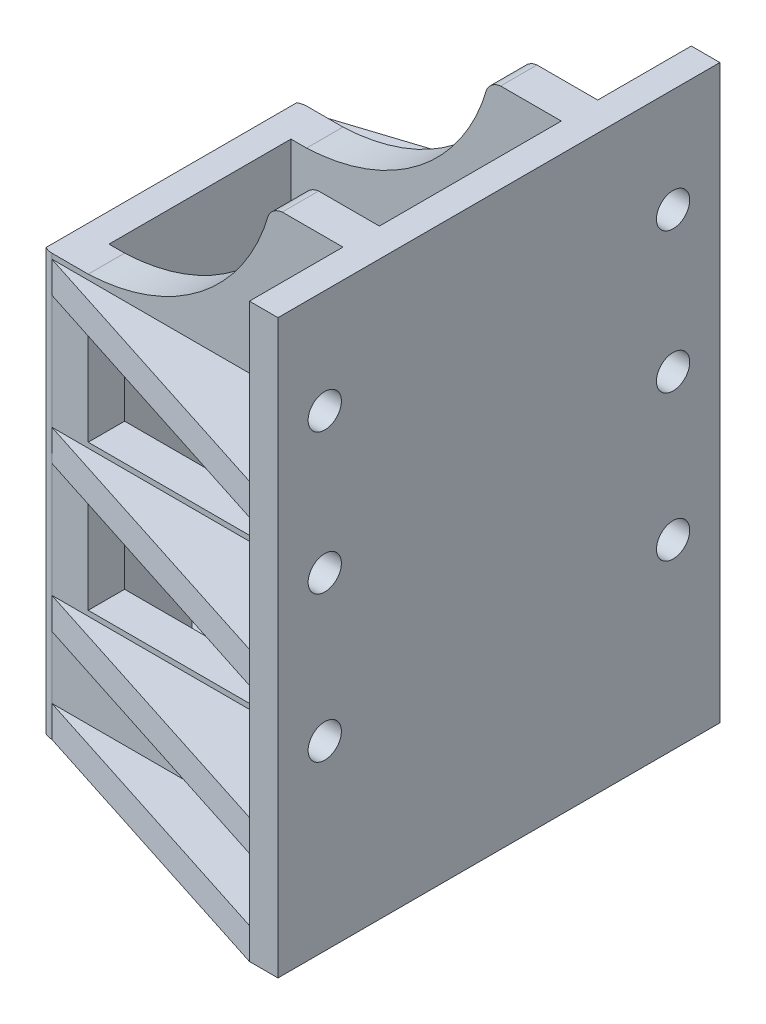
SolidWorks part; units mm, degrees
ref_plane "Plano frontal" through (0, 0, 0) normal (0, 0, 1) x (1, 0, 0)
ref_plane "Plano superior" through (0, 0, 0) normal (0, 1, 0) x (1, 0, 0)
ref_plane "Plano direito" through (0, 0, 0) normal (1, 0, 0) x (0, 0, -1)
sketch "Esboço1" plane through (0, 0, 0) normal (0, 1, 0) x (1, 0, 0)
  line L10 (15, 12.25) -> (16.5, 12.25)
  line L11 (-15, 12.25) -> (15, 12.25)
  line L12 (-16.5, 10.75) -> (-16.5, -10.75)
  line L13 (-15, -12.25) -> (15, -12.25)
  line L14 (16.5, 10.75) -> (16.5, -10.75)
  line L15 (16.5, 10.75) -> (16.5, 12.25)
  line L16 (15, -12.25) -> (16.5, -12.25)
  line L17 (16.5, -10.75) -> (16.5, -12.25)
  arc A2 (-16.5, -10.75) -> (-15, -12.25) centre (-15, -10.75) ccw
  arc A3 (-16.5, 10.75) -> (-15, 12.25) centre (-15, 10.75) cw
extrude "Ressalto-extrusão1" add sketch "Esboço1" along normal blind 55
sketch "Esboço2" plane through (0, 55, 0) normal (0, 1, 0) x (1, 0, 0)
  line L0 (-13, 8.75) -> (-13, -8.75)
  line L1 (13, 8.75) -> (13, -8.75)
  line L2 (-13, -8.75) -> (13, -8.75)
  line L3 (-13, 8.75) -> (13, 8.75)
extrude "Corte-extrusão1" cut sketch "Esboço2" against normal blind 52
sketch "Esboço3" plane through (-16.5, 0, 0) normal (-1, 0, 0) x (0, 0, 1)
  line L0 (-4.25, 8) -> (0.75, 8)
  line L1 (0.75, 8) -> (0.75, 3)
  line L2 (-4.25, 3) -> (0.75, 3)
  line L3 (-12.25, 3) -> (-12.25, 8)
  line L5 (-12.25, 3) -> (-4.25, 3)
  line L7 (-4.25, 8) -> (-12.25, 8)
extrude "Corte-extrusão2" cut sketch "Esboço3" against normal blind 29.5
sketch "Esboço4" plane through (0, 0, -12.25) normal (0, 0, -1) x (-1, 0, 0)
  line L0 (-11.5, 22.5) -> (-11.5, 12.5)
  line L1 (11.5, 36.5) -> (11.5, 26.5)
  line L2 (11.5, 40.5) -> (24.9424, 40.5)
  line L3 (11.5, 22.5) -> (11.5, 12.5)
  line L4 (-11.5, 36.5) -> (-11.5, 26.5)
  line L5 (24.9424, 40.5) -> (24.9424, 59.8345)
  line L6 (24.9424, 59.8345) -> (-1.5, 59.8345)
  line L7 (-16.5, 55) -> (-16.5, 57.6308)
  line L12 (-16.5, 57.6308) -> (-7.5761, 57.6308)
  line L15 (-11.5, 36.5) -> (11.5, 36.5)
  line L16 (-11.5, 26.5) -> (11.5, 26.5)
  line L17 (-11.5, 22.5) -> (11.5, 22.5)
  line L18 (-11.5, 12.5) -> (11.5, 12.5)
  line L21 (-6.0761, 62.0924) -> (-1.5, 59.8345)
  line L22 (-16.5, 55) -> (-7.5761, 55)
  line L23 (-6.0761, 62.0924) -> (-7.5761, 62.0924)
  line L24 (-7.5761, 62.0924) -> (-7.5761, 57.6308)
  line L25 (-7.5761, 55) -> (-7.1577, 55)
  arc A1 (-7.1577, 55) -> (-5.834, 54.0753) centre (-7.3669, 53.2908) cw
  arc A2 (-5.834, 54.0753) -> (11.5, 40.5) centre (12.2414, 59.301) ccw
extrude "Corte-extrusão3" cut sketch "Esboço4" against normal blind 52
sketch "Esboço5" plane through (0, 0, 0) normal (0, -1, 0) x (1, 0, 0)
  line L9 (-10, 8) -> (10, 8)
  line L10 (-10, 8) -> (-10, -8)
  line L11 (-10, -8) -> (10, -8)
  line L12 (10, 8) -> (10, -8)
extrude "Corte-extrusão4" cut sketch "Esboço5" against normal blind 52
sketch "Esboço6" plane through (0, 0, -12.25) normal (0, 0, -1) x (-1, 0, 0)
  line L2 (-16.5, 55) -> (-13, 55)
  line L12 (-8.2604, 40) -> (15, 40)
  line L13 (-8.2604, 37) -> (15, 37)
  line L14 (15, 26) -> (15, 23)
  line L15 (-8.2604, 40) -> (-13, 40)
  line L16 (15, 12) -> (15, 9)
  line L17 (-8.2604, 37) -> (-13, 37)
  line L18 (-8.2604, 26) -> (15, 26)
  line L19 (-8.2604, 26) -> (-13, 26)
  line L20 (-8.2604, 23) -> (-13, 23)
  line L21 (15, 3) -> (15, 0)
  line L22 (-8.2604, 23) -> (15, 23)
  line L23 (-16.5, 55) -> (-16.5, 0)
  line L24 (-8.2604, 12) -> (15, 12)
  line L25 (-8.2604, 12) -> (-13, 12)
  line L27 (-16.5, 0) -> (15, 0)
  line L28 (-13, 40) -> (-13, 55)
  line L29 (-8.2604, 9) -> (15, 9)
  line L30 (-8.2604, 9) -> (-13, 9)
  line L32 (-13, 3) -> (15, 3)
  line L33 (-13, 9) -> (-13, 3)
  line L34 (15, 40) -> (15, 37)
  line L35 (-13, 37) -> (-13, 26)
  line L37 (-13, 23) -> (-13, 12)
extrude "Ressalto-extrusão3" add sketch "Esboço6" along normal blind 9
sketch "Esboço9" plane through (0, 0, 12.25) normal (0, 0, 1) x (1, 0, 0)
  line L25 (13, 23) -> (13, 12)
  line L26 (13, 37) -> (13, 26)
  line L27 (-15, 40) -> (-15, 37)
  line L28 (13, 9) -> (13, 3)
  line L29 (13, 3) -> (-15, 3)
  line L30 (8.2604, 9) -> (13, 9)
  line L31 (8.2604, 9) -> (-15, 9)
  line L32 (13, 40) -> (13, 55)
  line L33 (16.5, 0) -> (-15, 0)
  line L34 (8.2604, 12) -> (13, 12)
  line L35 (8.2604, 12) -> (-15, 12)
  line L36 (16.5, 55) -> (16.5, 0)
  line L37 (8.2604, 23) -> (-15, 23)
  line L38 (-15, 3) -> (-15, 0)
  line L39 (8.2604, 23) -> (13, 23)
  line L40 (8.2604, 26) -> (13, 26)
  line L41 (8.2604, 26) -> (-15, 26)
  line L42 (8.2604, 37) -> (13, 37)
  line L43 (-15, 12) -> (-15, 9)
  line L44 (8.2604, 40) -> (13, 40)
  line L45 (-15, 26) -> (-15, 23)
  line L46 (8.2604, 37) -> (-15, 37)
  line L47 (8.2604, 40) -> (-15, 40)
  line L48 (16.5, 55) -> (13, 55)
extrude "Ressalto-extrusão4" add sketch "Esboço9" along normal blind 9
sketch "Esboço11" plane through (0, 55, 0) normal (0, 1, 0) x (1, 0, 0)
  line L0 (13, 21.25) -> (-15, 12.25)
  line L1 (-15, 12.25) -> (-18.3963, 13.557)
  line L2 (-18.3963, 13.557) -> (-20.171, 2.9688)
  line L3 (-20.171, 2.9688) -> (-21.6877, -13.9298)
  line L4 (-21.6877, -13.9298) -> (-19.2836, -16.808)
  line L5 (-19.2836, -16.808) -> (-15, -12.25)
  line L6 (-15, -12.25) -> (13, -21.25)
  line L7 (13, -21.25) -> (12.3873, -22.8422)
  line L8 (12.3873, -22.8422) -> (-13.7336, -25.767)
  line L9 (-13.7336, -25.767) -> (-25.5939, -17.7036)
  line L10 (-25.5939, -17.7036) -> (-24.1015, -8.7999)
  line L11 (-24.1015, -8.7999) -> (-21.4044, 21.25)
  line L12 (-21.4044, 21.25) -> (-11.3429, 26.8191)
  line L13 (-11.3429, 26.8191) -> (13.3468, 26.8191)
  line L14 (13.3468, 26.8191) -> (13, 21.25)
extrude "Corte-extrusão7" cut sketch "Esboço11" against normal through all
sketch "Esboço12" plane through (13, 0, 0) normal (-1, 0, 0) x (0, 0, 1)
  circle A0 centre (-16.75, 45) radius 1.6
  circle A1 centre (-16.75, 31.5) radius 1.6
  circle A2 centre (-16.75, 17.5) radius 1.6
  circle A3 centre (16.75, 17.5) radius 1.6
  circle A4 centre (16.75, 31.5) radius 1.6
  circle A5 centre (16.75, 45) radius 1.6
extrude "Corte-extrusão8" cut sketch "Esboço12" against normal through all
sketch "Esboço13" plane through (0, 0, -12.25) normal (0, 0, -1) x (-1, 0, 0)
  line L0 (-16, 57.7484) -> (-15.75, 57.7484)
  line L1 (-16.5, -2.7484) -> (-16, -2.7484)
  line L3 (-16, 57.7484) -> (-36.4816, 47.041)
  line L4 (16.5, -3.8191) -> (16, -3.8191)
  line L6 (16, 53.083) -> (35.3344, 35.1099)
  line L7 (35.3344, 35.1099) -> (36.9405, 23.6377)
  line L8 (36.9405, 23.6377) -> (28.757, 6.5059)
  line L9 (28.757, 6.5059) -> (16.5, -3.8191)
  line L10 (-36.4816, 47.041) -> (-32.9635, 30.8269)
  line L11 (-32.9635, 30.8269) -> (-32.0312, 26.5305)
  line L12 (-29.7512, 11.6301) -> (-26.2408, 1.764)
  line L13 (-26.2408, 1.764) -> (-21.5677, -3.8191)
  line L14 (-21.5677, -3.8191) -> (-16.5, -2.7484)
  line L15 (-32.0312, 26.5305) -> (-29.7512, 11.6301)
  line L16 (-15.75, 57.7484) -> (-15.75, -2.7484)
  line L17 (-16, -2.7484) -> (-15.75, -2.7484)
  line L18 (16, 53.083) -> (15.75, 53.083)
  line L19 (15.75, 53.083) -> (15.75, -9.9873)
  line L20 (15.75, -9.9873) -> (16, -3.8191)
extrude "Corte-extrusão9" cut sketch "Esboço13" against normal through all both and the other way through all
